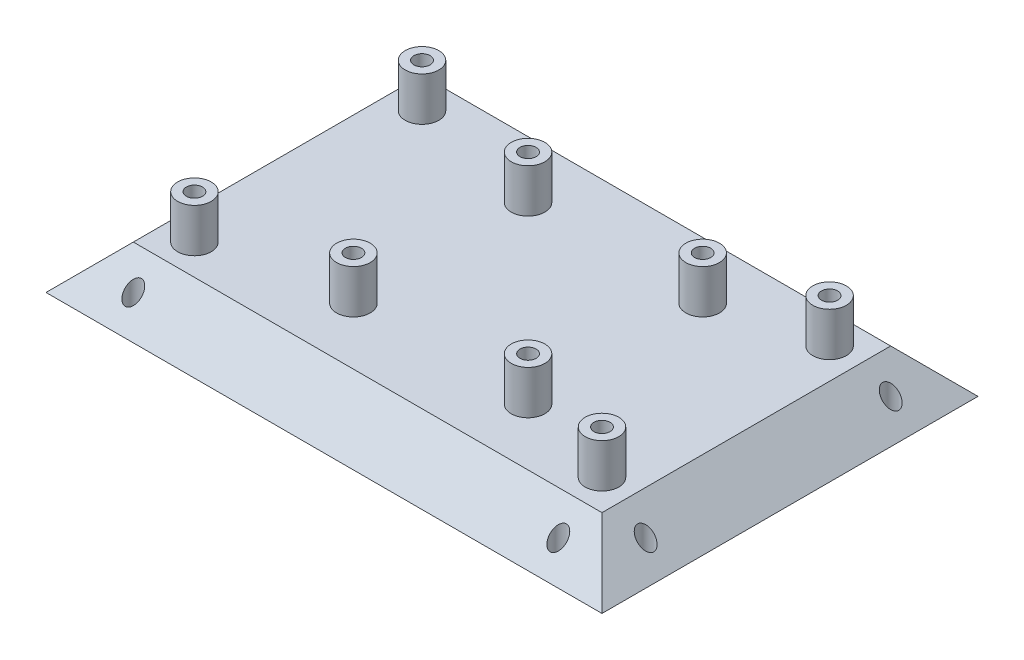
SolidWorks part; units mm, degrees
ref_plane "Спереди" through (0, 0, 0) normal (0, 0, 1) x (1, 0, 0)
ref_plane "Сверху" through (0, 0, 0) normal (0, 1, 0) x (1, 0, 0)
ref_plane "Справа" through (0, 0, 0) normal (1, 0, 0) x (0, 0, -1)
sketch "Sketch1" plane through (0, 0, 0) normal (0, 1, 0) x (1, 0, 0)
  line L1 (0, 0) -> (127.3501, 0)
  line L2 (0, 0) -> (0, -86.1254)
  line L3 (0, -86.1254) -> (127.3501, -86.1254)
  line L4 (127.3501, 0) -> (127.3501, -86.1254)
ref_plane "Plane1" through (0, 10, 0) normal (0, 1, 0) x (1, 0, 0)
sketch "Sketch2" plane through (0, 10, 0) normal (0, 1, 0) x (1, 0, 0)
  line L8 (10, -10) -> (10, -76.1254)
  line L9 (117.3501, -10) -> (10, -10)
  line L10 (117.3501, -76.1254) -> (117.3501, -10)
  line L11 (10, -76.1254) -> (117.3501, -76.1254)
  line L12 (10, -10) -> (10, -76.1254)
  line L13 (117.3501, -10) -> (10, -10)
  line L14 (117.3501, -76.1254) -> (117.3501, -10)
  line L15 (10, -76.1254) -> (117.3501, -76.1254)
  dimension "D1" = 10
loft "Loft1" add profiles "Sketch1", "Sketch2"
sketch "Sketch3" plane through (0, 0, 0) normal (0, -1, 0) x (1, 0, 0)
  line L0 (10, 10) -> (117.3501, 10) construction
  line L1 (0, 0) -> (127.3501, 0) construction
  line L2 (0, 0) -> (0, 86.1254) construction
  line L3 (0, 86.1254) -> (127.3501, 86.1254) construction
  line L4 (127.3501, 0) -> (127.3501, 86.1254) construction
  line L5 (117.3501, 10) -> (117.3501, 76.1254) construction
  line L6 (10, 76.1254) -> (117.3501, 76.1254) construction
  line L7 (10, 10) -> (10, 76.1254) construction
  line L8 (10, 10) -> (5, 10) construction
  line L9 (5, 10) -> (5, 15) construction
  line L10 (5, 15) -> (5, 20) construction
  line L11 (5, 20) -> (10, 20) construction
  line L12 (5, 15) -> (0, 15) construction
  line L13 (5, 15) -> (10, 15) construction
  line L14 (63.675, 0) -> (63.675, 86.1254) construction
  line L15 (0, 43.0627) -> (127.3501, 43.0627) construction
  line L16 (0, 0) -> (10, 10) construction
  circle A0 centre (5, 15) radius 1.85
  circle A1 centre (5, 71.1254) radius 1.85
  circle A2 centre (122.3501, 71.1254) radius 1.85
  circle A3 centre (122.3501, 15) radius 1.85
  circle A4 centre (15, 5) radius 1.85
  circle A5 centre (15, 81.1254) radius 1.85
  circle A6 centre (112.3501, 81.1254) radius 1.85
  circle A7 centre (112.3501, 5) radius 1.85
  dimension "D2" = 3.7
  dimension "D3" = 10
  dimension "D1" = 10
extrude "Cut-Extrude1" cut sketch "Sketch3" against normal through all
sketch "Sketch4" plane through (0, 10, 0) normal (0, 1, 0) x (1, 0, 0)
  line L0 (110.3501, -69.1254) -> (110.3501, -76.1254) construction
  line L1 (10, -76.1254) -> (117.3501, -76.1254) construction
  line L2 (110.3501, -69.1254) -> (117.3501, -69.1254) construction
  line L3 (117.3501, -76.1254) -> (117.3501, -10) construction
  line L4 (117.3501, -43.0627) -> (10, -43.0627) construction
  line L5 (10, -10) -> (10, -76.1254) construction
  line L6 (63.675, -76.1254) -> (63.675, -10) construction
  line L7 (117.3501, -10) -> (10, -10) construction
  circle A0 centre (110.3501, -69.1254) radius 1.85
  circle A1 centre (110.3501, -69.1254) radius 3.85
  circle A2 centre (110.3501, -17) radius 3.85
  circle A3 centre (110.3501, -17) radius 1.85
  circle A4 centre (17, -17) radius 1.85
  circle A5 centre (17, -17) radius 3.85
  circle A6 centre (17, -69.1254) radius 3.85
  circle A7 centre (17, -69.1254) radius 1.85
  dimension "D1" = 3.7
  dimension "D3" = 7
  dimension "D4" = 7
  dimension "D2" = 2
extrude "Boss-Extrude1" add sketch "Sketch4" along normal blind 10
sketch "Эскиз2" plane through (0, 10, 0) normal (0, 1, 0) x (1, 0, 0)
  line L0 (87.3501, -23.0627) -> (87.3501, -63.0627) construction
  line L1 (87.3501, -63.0627) -> (47.3501, -63.0627) construction
  line L2 (87.3501, -43.0627) -> (117.3501, -43.0627) construction
  line L3 (117.3501, -76.1254) -> (117.3501, -10) construction
  circle A0 centre (87.3501, -23.0627) radius 1.85
  circle A1 centre (87.3501, -23.0627) radius 3.85
  circle A2 centre (47.3501, -23.0627) radius 3.85
  circle A3 centre (47.3501, -23.0627) radius 1.85
  circle A4 centre (47.3501, -63.0627) radius 3.85
  circle A5 centre (47.3501, -63.0627) radius 1.85
  circle A6 centre (87.3501, -63.0627) radius 3.85
  circle A7 centre (87.3501, -63.0627) radius 1.85
  point P20 (67.3501, -63.0627)
  dimension "D1" = 3.7
  dimension "D3" = 2
  dimension "D5" = 50
  dimension "D6" = 40
  dimension "D7" = 40
  dimension "D2" = 2
  dimension "D4" = 2
extrude "Бобышка-Вытянуть1" add sketch "Эскиз2" along normal blind 10
